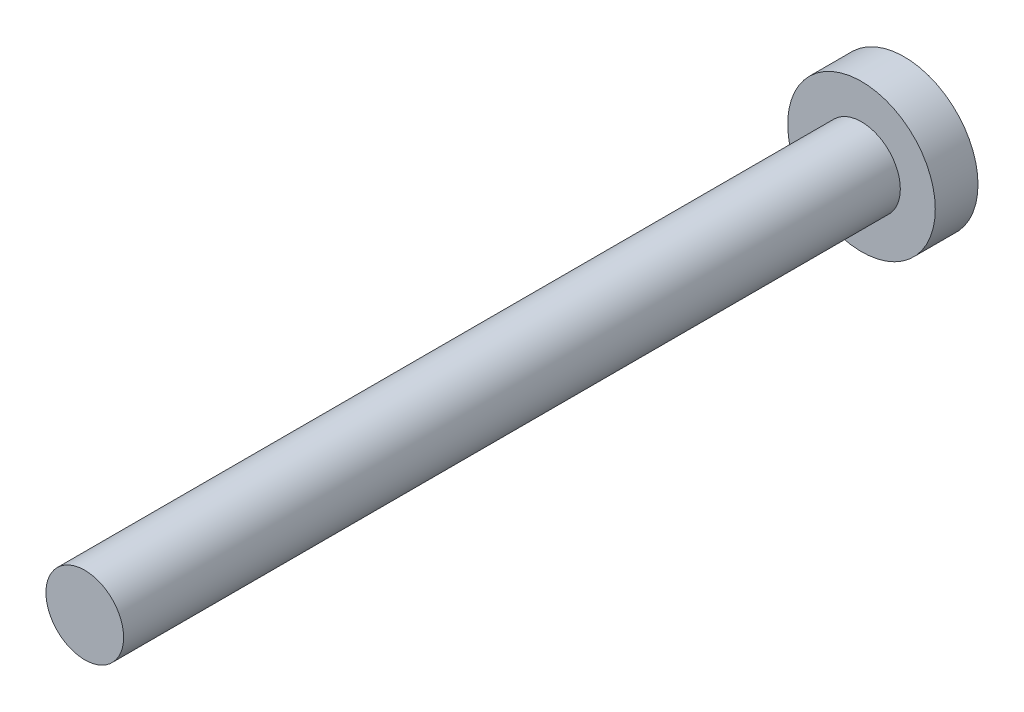
SolidWorks part; units mm, degrees
ref_plane "Front Plane" through (0, 0, 0) normal (0, 0, 1) x (1, 0, 0)
ref_plane "Top Plane" through (0, 0, 0) normal (0, 1, 0) x (1, 0, 0)
ref_plane "Right Plane" through (0, 0, 0) normal (1, 0, 0) x (0, 0, -1)
sketch "Low head envelope profile" plane through (0, 0, 0) normal (0, 0, 1) x (1, 0, 0)
  circle A0 centre (0, 0) radius 3.8
extrude "Low head envelope" add sketch "Low head envelope profile" along normal blind 2.2 from offset 2.2
sketch "M4 shank, threads omitted profile" plane through (0, 0, 0) normal (0, 0, 1) x (1, 0, 0)
  circle A0 centre (0, 0) radius 2
extrude "M4 shank, threads omitted" add sketch "M4 shank, threads omitted profile" along normal blind 40
